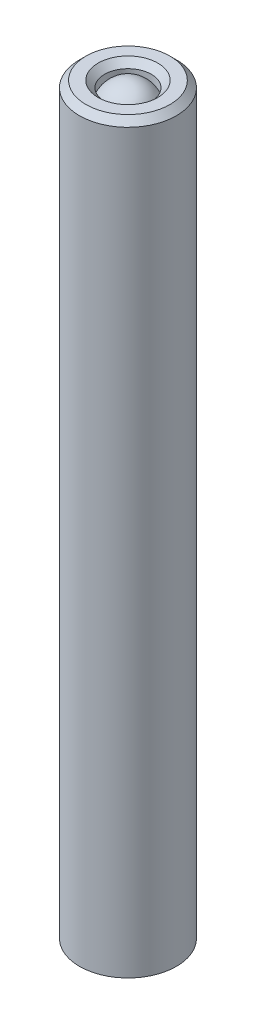
SolidWorks part; units mm, degrees
ref_plane "Front" through (0, 0, 0) normal (0, 0, 1) x (1, 0, 0)
ref_plane "Top" through (0, 0, 0) normal (0, 1, 0) x (1, 0, 0)
ref_plane "Right" through (0, 0, 0) normal (1, 0, 0) x (0, 0, -1)
sketch "Sketch1" plane through (0, 0, 0) normal (0, 1, 0) x (1, 0, 0)
  circle A0 centre (0, 0) radius 7.5
extrude "Boss-Extrude1" add sketch "Sketch1" along normal blind 115
sketch "Sketch2" plane through (0, 0, 0) normal (0, 0, 1) x (1, 0, 0)
  line L0 (0, 125.5152) -> (0, 102.6394) construction
  line L1 (-7.5, 115) -> (7.5, 115) construction
  line L2 (7.5, 115) -> (-7.5, 115) construction
  line L3 (-3.6186, 112.7046) -> (-3.6186, 116.7627)
  line L5 (-3.6186, 116.7627) -> (0, 116.7627)
  line L6 (0, 116.7627) -> (0, 115)
  circle A0 centre (0, 111) radius 4 construction
  arc A1 (0, 115) -> (-3.6186, 112.7046) centre (0, 111) ccw
revolve "Cut-Revolve1" cut sketch "Sketch2" angle 360 about L0
chamfer "Chamfer1" distance 1 angle 45 2 edges at (0, 115, 7.5) (0, 115, 3.6186)
